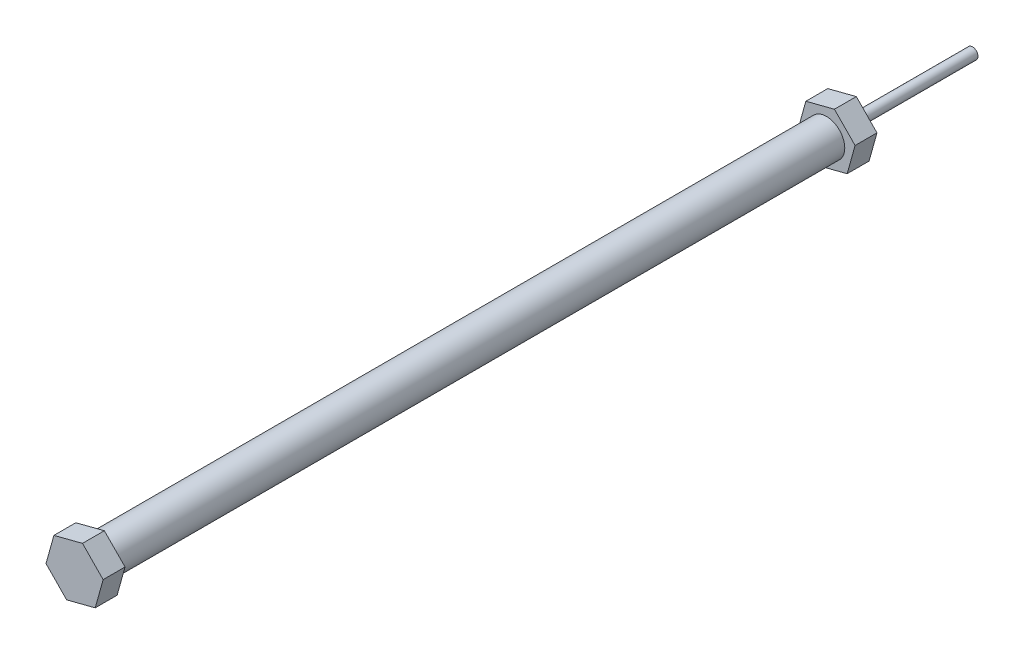
SolidWorks part; units mm, degrees
ref_plane "前基準面" through (0, 0, 0) normal (0, 0, 1) x (1, 0, 0)
ref_plane "上基準面" through (0, 0, 0) normal (0, 1, 0) x (1, 0, 0)
ref_plane "右基準面" through (0, 0, 0) normal (1, 0, 0) x (0, 0, -1)
sketch "草圖1" plane through (0, 0, 0) normal (0, 0, 1) x (1, 0, 0)
  circle A0 centre (0, 0) radius 2.5
  dimension "D1" = 5
extrude "填料-伸長1" add sketch "草圖1" along normal blind 100
sketch "草圖2" plane through (0, 0, 0) normal (0, 0, 1) x (1, 0, 0)
  line L1 (2.8307, -2.8845) -> (3.9134, 1.0092)
  line L2 (3.9134, 1.0092) -> (1.0828, 3.8937)
  line L3 (1.0828, 3.8937) -> (-2.8307, 2.8845)
  line L4 (-2.8307, 2.8845) -> (-3.9134, -1.0092)
  line L5 (-3.9134, -1.0092) -> (-1.0828, -3.8937)
  line L6 (-1.0828, -3.8937) -> (2.8307, -2.8845)
  circle A0 centre (0, 0) radius 3.5 construction
  dimension "D1" = 7
sketch "草圖3" plane through (0, 0, 0) normal (0, 0, 1) x (1, 0, 0)
  line L0 (1.0828, 3.8937) -> (-2.8307, 2.8845) construction
  line L1 (3.9134, 1.0092) -> (1.0828, 3.8937) construction
  line L2 (2.8307, -2.8845) -> (3.9134, 1.0092) construction
  line L3 (-1.0828, -3.8937) -> (2.8307, -2.8845) construction
  line L4 (-3.9134, -1.0092) -> (-1.0828, -3.8937) construction
  line L5 (-2.8307, 2.8845) -> (-3.9134, -1.0092) construction
  line L6 (1.0828, 3.8937) -> (-2.8307, 2.8845)
  line L7 (3.9134, 1.0092) -> (1.0828, 3.8937)
  line L8 (2.8307, -2.8845) -> (3.9134, 1.0092)
  line L9 (-1.0828, -3.8937) -> (2.8307, -2.8845)
  line L10 (-3.9134, -1.0092) -> (-1.0828, -3.8937)
  line L11 (-2.8307, 2.8845) -> (-3.9134, -1.0092)
extrude "填料-伸長2" add sketch "草圖3" against normal blind 3
sketch "草圖4" plane through (0, 0, 0) normal (0, 0, 1) x (1, 0, 0)
  line L0 (-2.8307, 2.8845) -> (-3.9134, -1.0092) construction
  line L1 (-3.9134, -1.0092) -> (-1.0828, -3.8937) construction
  line L2 (-1.0828, -3.8937) -> (2.8307, -2.8845) construction
  line L3 (2.8307, -2.8845) -> (3.9134, 1.0092) construction
  line L4 (3.9134, 1.0092) -> (1.0828, 3.8937) construction
  line L5 (1.0828, 3.8937) -> (-2.8307, 2.8845) construction
  line L6 (-2.8307, 2.8845) -> (-3.9134, -1.0092)
  line L7 (-3.9134, -1.0092) -> (-1.0828, -3.8937)
  line L8 (-1.0828, -3.8937) -> (2.8307, -2.8845)
  line L9 (2.8307, -2.8845) -> (3.9134, 1.0092)
  line L10 (3.9134, 1.0092) -> (1.0828, 3.8937)
  line L11 (1.0828, 3.8937) -> (-2.8307, 2.8845)
extrude "填料-伸長3" add sketch "草圖4" along normal blind 3 from surface at 100 starting at face at (2.5, 0, 100)
sketch "草圖5" plane through (0, 0, 0) normal (0, 0, 1) x (1, 0, 0)
  circle A0 centre (0, 0) radius 0.75
  dimension "D1" = 1.5
extrude "填料-伸長4" add sketch "草圖5" against normal blind 20
